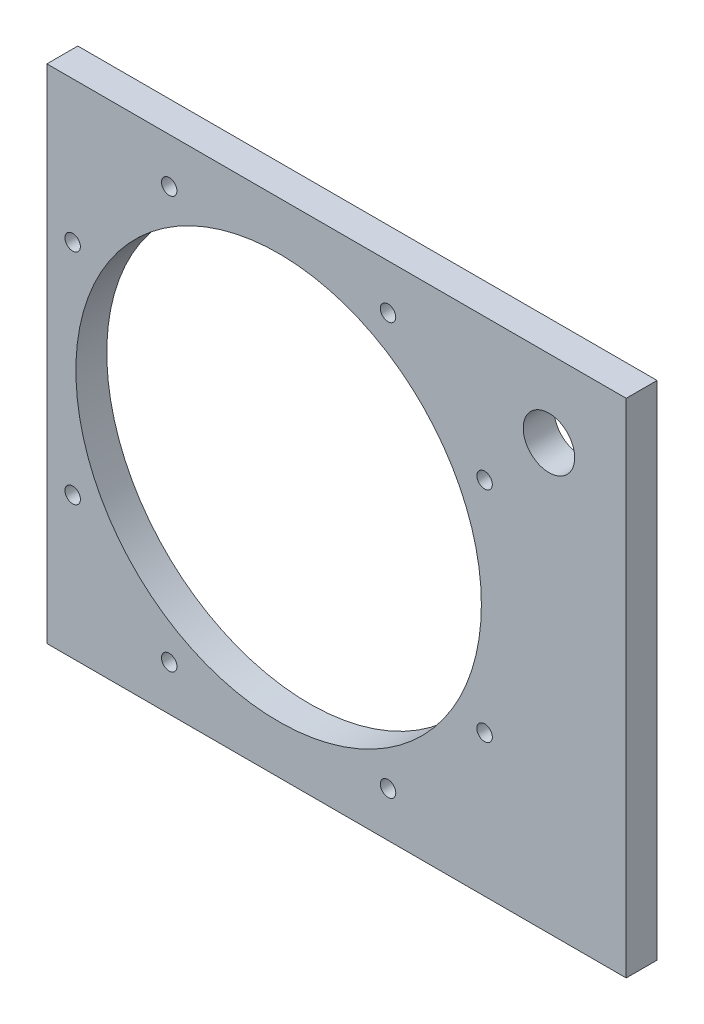
SolidWorks part; units mm, degrees
ref_plane "前视基准面" through (0, 0, 0) normal (0, 0, 1) x (1, 0, 0)
ref_plane "上视基准面" through (0, 0, 0) normal (0, 1, 0) x (1, 0, 0)
ref_plane "右视基准面" through (0, 0, 0) normal (1, 0, 0) x (0, 0, -1)
other "Configuration Table"
sketch "草图1" plane through (0, 0, 0) normal (0, 0, 1) x (1, 0, 0)
  line L0 (-225, 0) -> (0, 0) construction
  line L1 (-225, 195) -> (225, 195)
  line L2 (-225, 195) -> (-225, -195)
  line L3 (-225, -195) -> (225, -195)
  line L4 (225, 195) -> (225, -195)
  line L5 (-225, 195) -> (225, -195) construction
  line L6 (-225, -195) -> (225, 195) construction
  line L7 (0, 0) -> (0, 195) construction
  line L8 (-45, 0) -> (-45, 195) construction
  circle A0 centre (-45, 0) radius 157.5
  circle A3 centre (-205, 85) radius 6
  circle A4 centre (-205, -85) radius 6
  circle A5 centre (40, 160) radius 6
  circle A6 centre (-130, 160) radius 6
  circle A7 centre (115, -85) radius 6
  circle A8 centre (115, 85) radius 6
  circle A9 centre (-130, -160) radius 6
  circle A10 centre (40, -160) radius 6
  circle A11 centre (165, 135) radius 20
  point P0 (0, 0)
  point P31 (-45, 0)
  dimension "D3" = 315
  dimension "D5" = 12
  dimension "D11" = 40
  dimension "D1" = 450
  dimension "D2" = 390
  dimension "D4" = 180
  dimension "D6" = 4
  dimension "D7" = 170
  dimension "D8" = 320
  dimension "D9" = 60
  dimension "D10" = 60
extrude "凸台-拉伸1" add sketch "草图1" along normal blind 24
